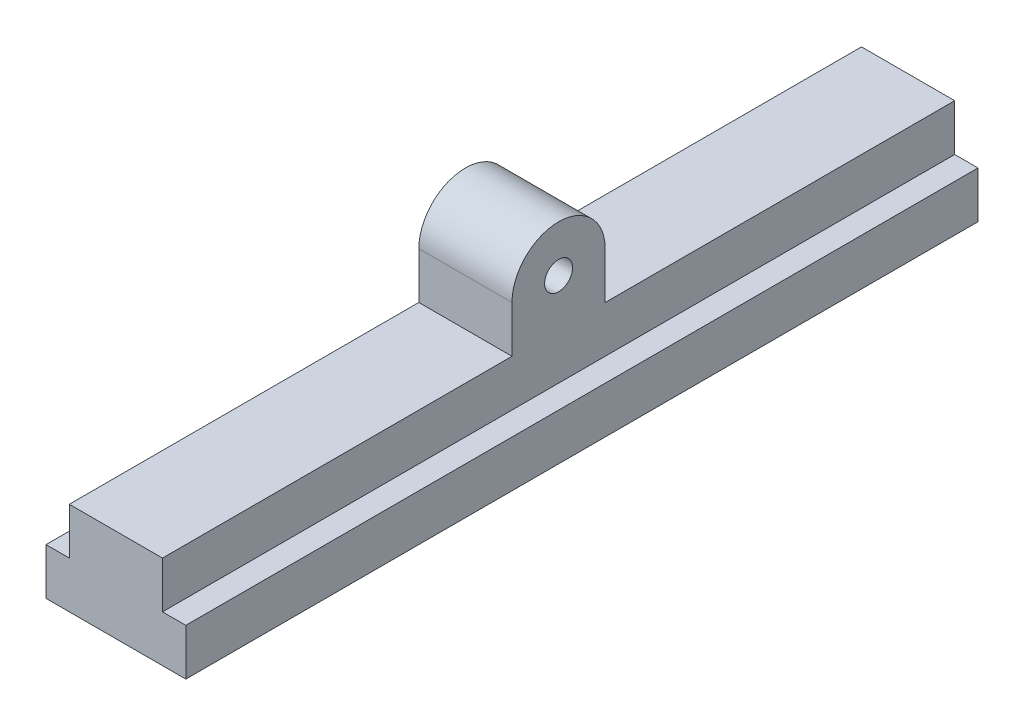
SolidWorks part; units mm, degrees
ref_plane "前视基准面" through (0, 0, 0) normal (0, 0, 1) x (1, 0, 0)
ref_plane "上视基准面" through (0, 0, 0) normal (0, 1, 0) x (1, 0, 0)
ref_plane "右视基准面" through (0, 0, 0) normal (1, 0, 0) x (0, 0, -1)
other "Configuration Table"
sketch "草图1" plane through (0, 0, 0) normal (0, 0, 1) x (1, 0, 0)
  line L0 (24.987, -11.866) -> (-5.013, -11.866)
  line L1 (-5.013, -11.866) -> (-5.013, -1.866)
  line L2 (-5.013, -1.866) -> (-0.013, -1.866)
  line L3 (-0.013, -1.866) -> (-0.013, 8.134)
  line L4 (-0.013, 8.134) -> (19.987, 8.134)
  line L5 (19.987, 8.134) -> (19.987, -1.866)
  line L6 (19.987, -1.866) -> (24.987, -1.866)
  line L7 (24.987, -1.866) -> (24.987, -11.866)
extrude "凸台-拉伸3" add sketch "草图1" along normal blind 240
sketch "草图4" plane through (0, 0, 0) normal (0, 0, -1) x (-1, 0, 0)
  line L0 (-19.987, 8.134) -> (0.013, 8.134)
  line L1 (0.013, 8.134) -> (0.013, -1.866)
  line L2 (0.013, -1.866) -> (5.013, -1.866)
  line L3 (5.013, -1.866) -> (5.013, -11.866)
  line L4 (5.013, -11.866) -> (-24.987, -11.866)
  line L5 (-24.987, -11.866) -> (-24.987, -1.866)
  line L6 (-24.987, -1.866) -> (-19.987, -1.866)
  line L7 (-19.987, -1.866) -> (-19.987, 8.134)
extrude "凸台-拉伸5" add sketch "草图4" along normal blind 100
ref_plane "基准面1" through (19.987, 8.134, 240) normal (0, 0, -1) x (-1, 0, 0)
sketch "草图9" plane through (0, -11.866, 0) normal (0, -1, 0) x (1, 0, 0)
  line L0 (24.987, -100) -> (24.987, 70)
  line L1 (24.987, 240) -> (24.987, -100) construction
  line L2 (-5.013, -100) -> (-5.013, 70)
  line L3 (-5.013, 240) -> (-5.013, -100) construction
  line L4 (-5.013, 70) -> (24.987, 70)
  line L5 (-5.013, -100) -> (24.987, -100)
extrude "切除-拉伸1" cut sketch "草图9" against normal blind 60
sketch "草图11" plane through (19.987, 0, 0) normal (1, 0, 0) x (0, 0, -1)
  line L0 (-240, 8.134) -> (-165, 8.134)
  line L1 (-240, 8.134) -> (-70, 8.134) construction
  line L2 (-165, 8.134) -> (-165, 18.134)
  line L3 (-70, 8.134) -> (-145, 8.134)
  line L4 (-145, 8.134) -> (-145, 18.134)
  line L5 (-165, 18.134) -> (-145, 18.134)
  circle A0 centre (-155, 18.134) radius 10
  circle A1 centre (-155, 18.134) radius 3
  line M7 (-70, 8.134) -> (-240, 8.134)
extrude "凸台-拉伸6" add sketch "草图11" against normal blind 20 contours A1 L5 A0 | A1 L5 A0 | A0 L4 M7 | A0 L2 M7
